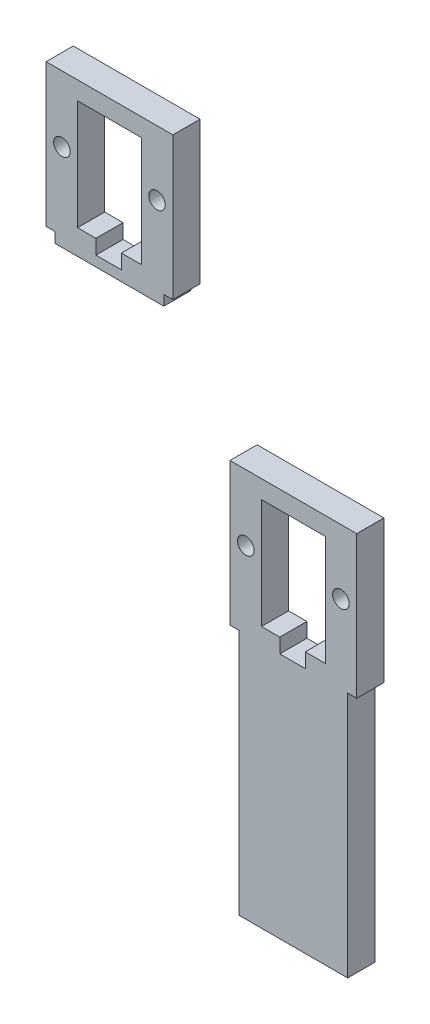
SolidWorks part; units mm, degrees
ref_plane "Front Plane" through (0, 0, 0) normal (0, 0, 1) x (1, 0, 0)
ref_plane "Top Plane" through (0, 0, 0) normal (0, 1, 0) x (1, 0, 0)
ref_plane "Right Plane" through (0, 0, 0) normal (1, 0, 0) x (0, 0, -1)
sketch "Sketch1" plane through (0, 0, 0) normal (0, 0, 1) x (1, 0, 0)
  line L0 (3.7679, -62.8696) -> (-8.2321, -62.8696)
  line L2 (-8.2321, 23.1304) -> (3.7679, 23.1304)
  line L3 (3.7679, 23.1304) -> (15.7679, 23.1304)
  line L5 (15.7679, -62.8696) -> (3.7679, -62.8696)
  line L6 (3.7679, 19.1304) -> (-3.2871, 19.1304)
  line L7 (-3.2871, 19.1304) -> (-3.2871, -5.1596)
  line L10 (10.8229, -5.1596) -> (10.8229, 19.1304)
  line L11 (10.8229, 19.1304) -> (3.7679, 19.1304)
  line L12 (-8.2321, -8.3743) -> (-10.2321, -8.3743)
  line L13 (-10.2321, -8.3743) -> (-10.2321, 23.1304)
  line L14 (-10.2321, 23.1304) -> (-8.2321, 23.1304)
  line L15 (15.7679, -8.3743) -> (17.7679, -8.3743)
  line L16 (17.7679, -8.3743) -> (17.7679, 23.1304)
  line L17 (17.7679, 23.1304) -> (15.7679, 23.1304)
  line L18 (15.7679, -8.3743) -> (15.7679, -62.8696)
  line L19 (-8.2321, -8.3743) -> (-8.2321, -62.8696)
  line L20 (0.7686, -5.1596) -> (0.7686, -8.3743)
  line L21 (0.7686, -8.3743) -> (6.3999, -8.3743)
  line L22 (6.3999, -8.3743) -> (6.3999, -5.1596)
  line L23 (6.3999, -5.1596) -> (10.8229, -5.1596)
  line L24 (0.7686, -5.1596) -> (-3.2871, -5.1596)
  circle A0 centre (-6.7321, 8.5752) radius 1.825
  circle A1 centre (14.2679, 8.8706) radius 1.825
  dimension "D3" = 3.65
  dimension "D8" = 10.5
  dimension "D9" = 21
  dimension "D1" = 24.29
  dimension "D4" = 86
  dimension "D5" = 12
  dimension "D6" = 4
  dimension "D7" = 2
  dimension "D10" = 7.055
extrude "Boss-Extrude1" add sketch "Sketch1" along normal blind 6
sketch "Sketch3" plane through (0, 0, 0) normal (0, 0, 1) x (1, 0, 0)
  line L0 (-36.8447, 45.325) -> (-48.8447, 45.325)
  line L1 (-48.8447, 79.1029) -> (-36.8447, 79.1029)
  line L2 (-36.8447, 79.1029) -> (-24.8447, 79.1029)
  line L3 (-24.8447, 45.325) -> (-36.8447, 45.325)
  line L4 (-36.8447, 75.1029) -> (-43.8997, 75.1029)
  line L5 (-43.8997, 75.1029) -> (-43.8997, 50.8129)
  line L6 (-29.7897, 50.8129) -> (-29.7897, 75.1029)
  line L7 (-29.7897, 75.1029) -> (-36.8447, 75.1029)
  line L8 (-48.8447, 47.5982) -> (-50.8447, 47.5982)
  line L9 (-50.8447, 47.5982) -> (-50.8447, 79.1029)
  line L10 (-50.8447, 79.1029) -> (-48.8447, 79.1029)
  line L11 (-24.8447, 47.5982) -> (-22.8447, 47.5982)
  line L12 (-22.8447, 47.5982) -> (-22.8447, 79.1029)
  line L13 (-22.8447, 79.1029) -> (-24.8447, 79.1029)
  line L14 (-24.8447, 47.5982) -> (-24.8447, 45.325)
  line L15 (-48.8447, 47.5982) -> (-48.8447, 45.325)
  line L16 (-39.844, 50.8129) -> (-39.844, 47.5982)
  line L17 (-39.844, 47.5982) -> (-34.2127, 47.5982)
  line L18 (-34.2127, 47.5982) -> (-34.2127, 50.8129)
  line L19 (-34.2127, 50.8129) -> (-29.7897, 50.8129)
  line L20 (-39.844, 50.8129) -> (-43.8997, 50.8129)
  circle A0 centre (-47.3447, 64.5477) radius 1.825
  circle A1 centre (-26.3447, 64.8431) radius 1.825
  dimension "D2" = 3.65
  dimension "D1" = 24.29
  dimension "D4" = 12
  dimension "D5" = 4
  dimension "D6" = 10.5
  dimension "D7" = 21
  dimension "D8" = 7.055
  dimension "D9" = 2
extrude "Boss-Extrude2" add sketch "Sketch3" along normal blind 6 separate body
